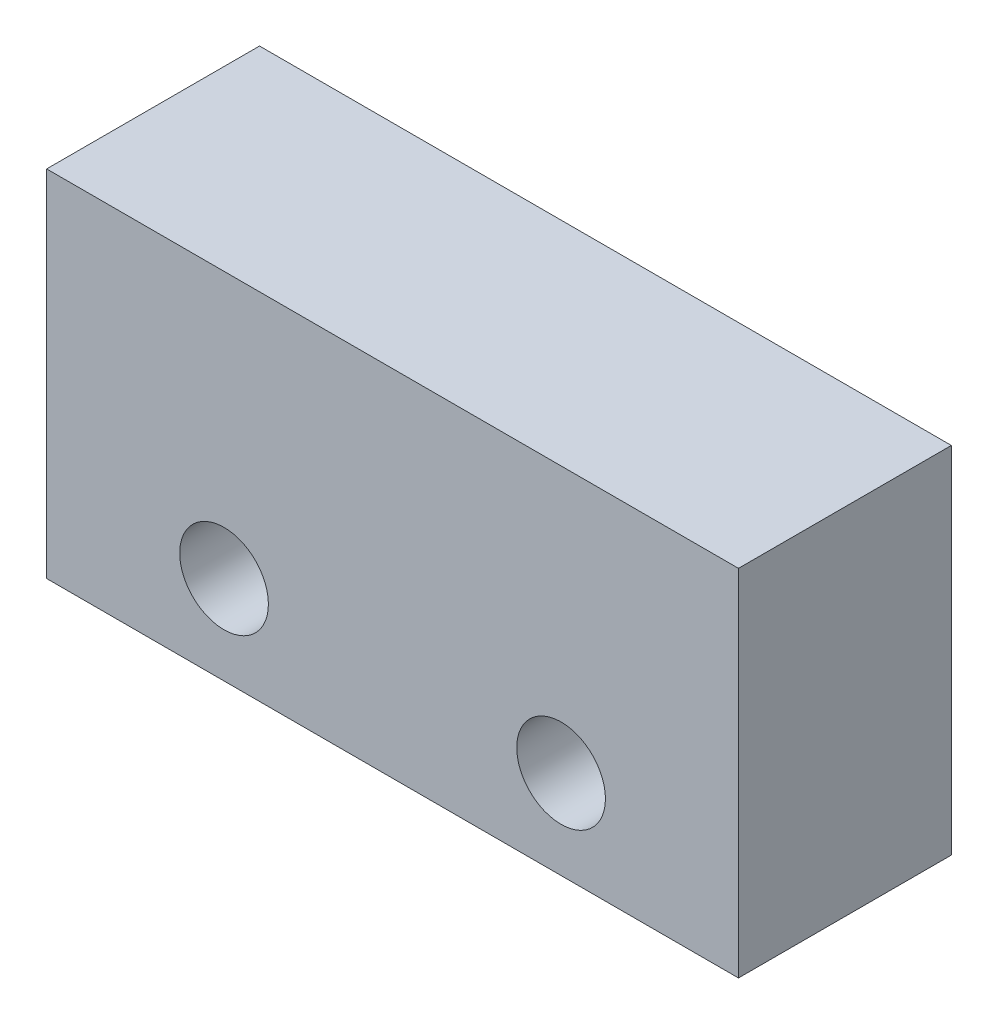
SolidWorks part; units mm, degrees
ref_plane "Front Plane" through (0, 0, 0) normal (0, 0, 1) x (1, 0, 0)
ref_plane "Top Plane" through (0, 0, 0) normal (0, 1, 0) x (1, 0, 0)
ref_plane "Right Plane" through (0, 0, 0) normal (1, 0, 0) x (0, 0, -1)
sketch "Sketch2" plane through (0, 0, 0) normal (0, 0, 1) x (1, 0, 0)
  line L0 (-4.75, -2.5) -> (4.75, -2.5) construction
  line L1 (-9.75, -5) -> (9.75, -5)
  line L2 (-9.75, -5) -> (-9.75, 5)
  line L3 (-9.75, 5) -> (9.75, 5)
  line L4 (9.75, -5) -> (9.75, 5)
  line L5 (-9.75, -5) -> (9.75, 5) construction
  line L6 (-9.75, 5) -> (9.75, -5) construction
  circle A0 centre (-4.75, -2.5) radius 1.25
  circle A1 centre (4.75, -2.5) radius 1.25
  point P0 (0, 0)
  dimension "D6" = 2.5
  dimension "D1" = 19.5
  dimension "D2" = 10
  dimension "D3" = 5
  dimension "D4" = 5
  dimension "D5" = 2.5
extrude "Boss-Extrude1" add sketch "Sketch2" along normal mid plane 6
